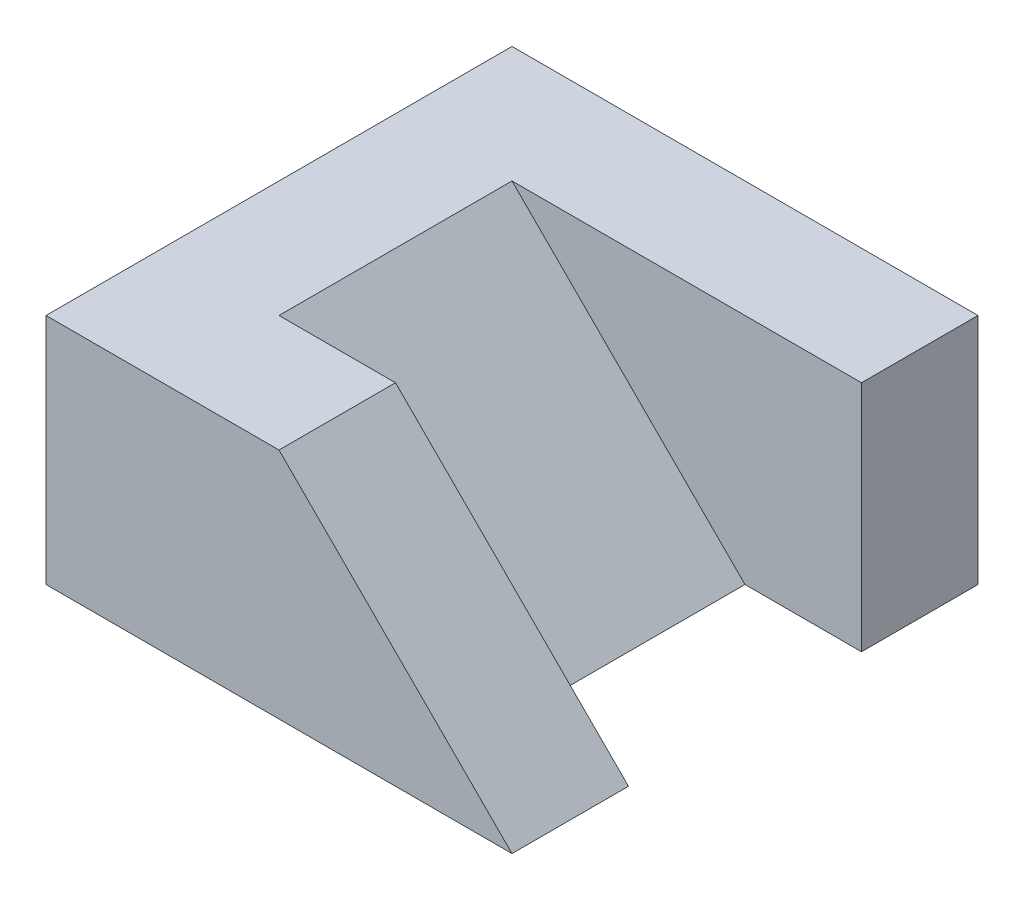
SolidWorks part; units mm, degrees
ref_plane "前基準面" through (0, 0, 0) normal (0, 0, 1) x (1, 0, 0)
ref_plane "上基準面" through (0, 0, 0) normal (0, 1, 0) x (1, 0, 0)
ref_plane "右基準面" through (0, 0, 0) normal (1, 0, 0) x (0, 0, -1)
sketch "草圖1" plane through (0, 0, 0) normal (0, 0, 1) x (1, 0, 0)
  line L1 (0, 0) -> (20, 0)
  line L2 (0, 0) -> (0, 10)
  line L3 (0, 10) -> (20, 10)
  line L4 (20, 0) -> (20, 10)
  dimension "D1" = 10
  dimension "D2" = 20
extrude "填料-伸長1" add sketch "草圖1" along normal blind 5
sketch "草圖2" plane through (0, 0, 5) normal (0, 0, 1) x (1, 0, 0)
  line L0 (20, 10) -> (0, 10) construction
  line L1 (0, 0) -> (5, 0)
  line L2 (0, 0) -> (0, 10)
  line L3 (0, 10) -> (5, 10)
  line L4 (5, 0) -> (5, 10)
  dimension "D1" = 5
extrude "填料-伸長2" add sketch "草圖2" along normal blind 10
sketch "草圖3" plane through (0, 0, 15) normal (0, 0, 1) x (1, 0, 0)
  line L1 (0, 0) -> (20, 0)
  line L2 (0, 0) -> (0, 10)
  line L3 (0, 10) -> (10, 10)
  line L4 (5, 0) -> (20, 0) construction
  line L5 (10, 10) -> (20, 0)
  line L6 (20, 10) -> (5, 10) construction
  point P1 (17.9617, 0)
  point P5 (0, 0)
  point P6 (15.5519, 0)
  point P11 (10, 10.6966)
  dimension "D1" = 10
extrude "填料-伸長3" add sketch "草圖3" along normal blind 5
ref_plane "平面1" through (0, 0, 10) normal (0, 0, 1) x (1, 0, 0)
sketch "草圖4" plane through (0, 0, 10) normal (0, 0, 1) x (1, 0, 0)
  line L0 (0, 0) -> (0, 10)
  line L1 (0, 10) -> (5, 10)
  line L2 (10, 10) -> (0, 10) construction
  line L3 (5, 10) -> (15, 0)
  line L4 (0, 0) -> (20, 0) construction
  line L5 (15, 0) -> (0, 0)
  line L6 (20, 0) -> (10, 10) construction
  dimension "D1" = 5
extrude "填料-伸長4" add sketch "草圖4" along normal mid plane 10
